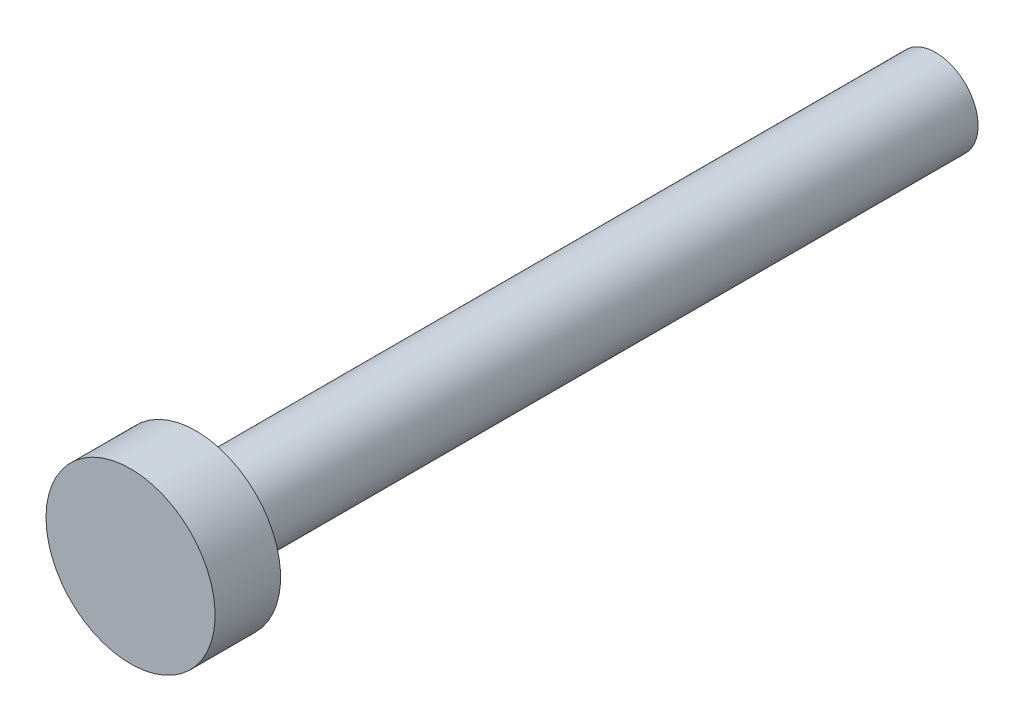
SolidWorks part; units mm, degrees
ref_plane "Plan de face" through (0, 0, 0) normal (0, 0, 1) x (1, 0, 0)
ref_plane "Plan de dessus" through (0, 0, 0) normal (0, 1, 0) x (1, 0, 0)
ref_plane "Plan de droite" through (0, 0, 0) normal (1, 0, 0) x (0, 0, -1)
sketch "Esquisse1" plane through (0, 0, 0) normal (0, 0, 1) x (1, 0, 0)
  circle A0 centre (0, 0) radius 4
  dimension "D1" = 8
extrude "Boss.-Extru.1" add sketch "Esquisse1" along normal blind 3.1
sketch "Esquisse2" plane through (0, 0, 0) normal (0, 0, -1) x (-1, 0, 0)
  circle A0 centre (0, 0) radius 2
  dimension "D1" = 4
extrude "Boss.-Extru.2" add sketch "Esquisse2" along normal blind 35
